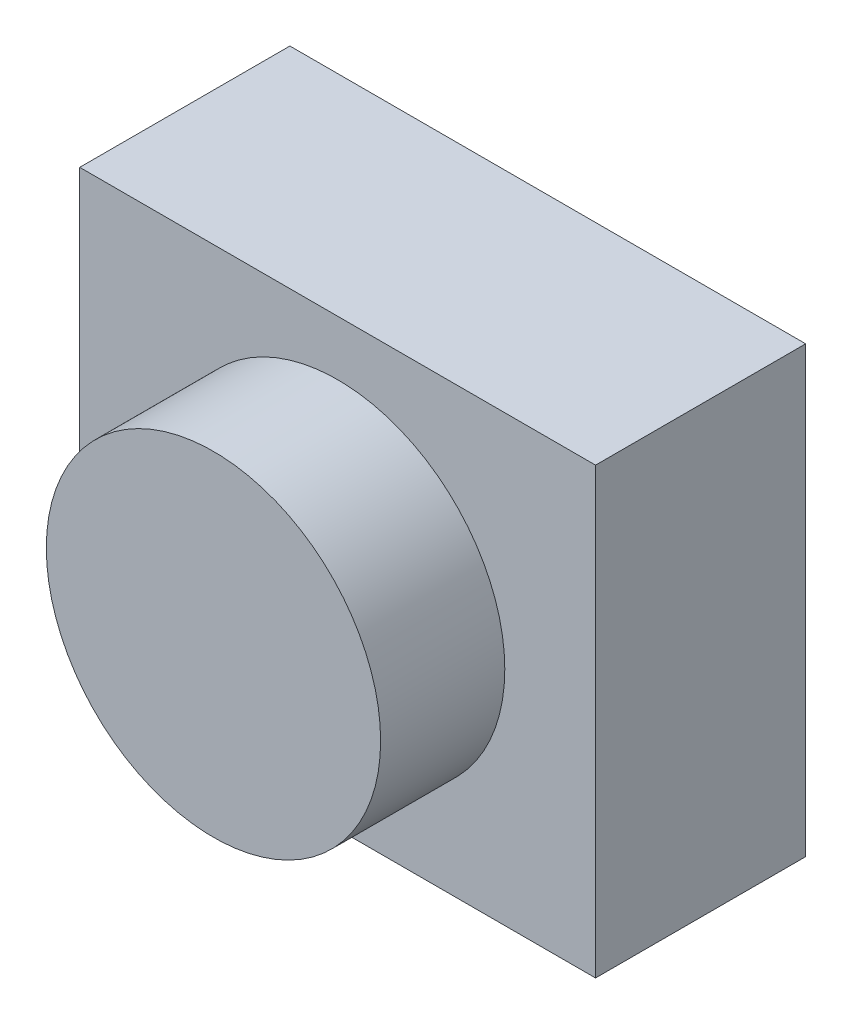
SolidWorks part; units mm, degrees
ref_plane "Front Plane" through (0, 0, 0) normal (0, 0, 1) x (1, 0, 0)
ref_plane "Top Plane" through (0, 0, 0) normal (0, 1, 0) x (1, 0, 0)
ref_plane "Right Plane" through (0, 0, 0) normal (1, 0, 0) x (0, 0, -1)
sketch "Esquisse1" plane through (0, 0, 0) normal (0, 0, 1) x (1, 0, 0)
  line L1 (-27, 23.25) -> (27, 23.25)
  line L2 (-27, 23.25) -> (-27, -23.25)
  line L3 (-27, -23.25) -> (27, -23.25)
  line L4 (27, 23.25) -> (27, -23.25)
  line L5 (-27, 23.25) -> (27, -23.25) construction
  line L6 (-27, -23.25) -> (27, 23.25) construction
  point P0 (0, 0)
  dimension "D1" = 46.5
  dimension "D2" = 54
extrude "Boss.-Extru.1" add sketch "Esquisse1" along normal blind 22
sketch "Esquisse2" plane through (0, 0, 22) normal (0, 0, 1) x (1, 0, 0)
  circle A0 centre (0, 0) radius 17.5
  dimension "D1" = 35
extrude "Boss.-Extru.2" add sketch "Esquisse2" along normal blind 13
